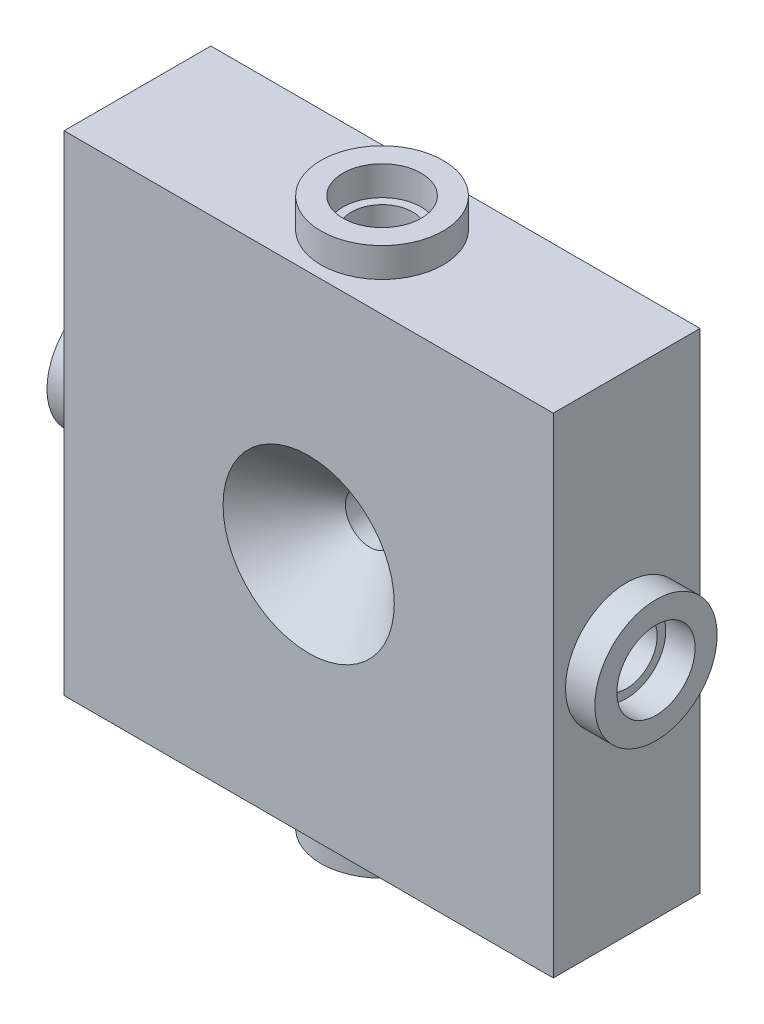
SolidWorks part; units mm, degrees
material "6063-T5"
ref_plane "正面" through (0, 0, 0) normal (0, 0, 1) x (1, 0, 0)
ref_plane "平面" through (0, 0, 0) normal (0, 1, 0) x (1, 0, 0)
ref_plane "右側面" through (0, 0, 0) normal (1, 0, 0) x (0, 0, -1)
sketch "ｽｹｯﾁ1" plane through (0, 0, 0) normal (0, 0, 1) x (1, 0, 0)
  line L1 (-10, 10) -> (10, 10)
  line L2 (-10, 10) -> (-10, -10)
  line L3 (-10, -10) -> (10, -10)
  line L4 (10, 10) -> (10, -10)
  line L5 (-10, 10) -> (10, -10) construction
  line L6 (-10, -10) -> (10, 10) construction
  circle A0 centre (0, 0) radius 1
  point P0 (0, 0)
  dimension "D2" = 2
  dimension "D1" = 20
extrude "ﾎﾞｽ - 押し出し1" add sketch "ｽｹｯﾁ1" along normal blind 3
sketch "ｽｹｯﾁ2" plane through (0, 0, 0) normal (0, 1, 0) x (1, 0, 0)
  line L1 (-1, -0.5) -> (-4.5, -3) construction
  line L2 (1, 0) -> (-1, 0) construction
  line L3 (1, 0) -> (-1, 0) construction
  line L4 (1, -0.5) -> (0, -0.5)
  line L5 (10, -3) -> (-10, -3) construction
  line L6 (0, -3) -> (3.5, -3)
  line L7 (3.5, -3) -> (1, -0.5)
  line L8 (0, -0.5) -> (0, -3)
  line L9 (-4.5, -3) -> (0, -3) construction
  line L10 (0, -0.5) -> (-1, -0.5) construction
  dimension "D2" = 45
  dimension "D3" = 0.5
  dimension "D1" = 2
revolve "ｶｯﾄ - 回転1" cut sketch "ｽｹｯﾁ2" angle 360 about L8
mirror "ﾐﾗｰ1" about plane through (0, 0, 0) normal (0, 0, 1) of bodies 103
hole_wizard "M3x0.5 ねじ穴1" positions "ｽｹｯﾁ4" profile "ｽｹｯﾁ5" tap size "M3x0.5" standard "JIS"
sketch "ｽｹｯﾁ4" plane through (-10, 0, 0) normal (-1, 0, 0) x (0, 0, 1)
  point P0 (0, 0)
sketch "ｽｹｯﾁ5" plane through (-10, 0, 0) normal (0, 1, 0) x (0, 0, 1)
  line L0 (0, 0) -> (0, 6.7511)
  line L1 (0, 6.7511) -> (1.25, 6)
  line L2 (1.25, 6) -> (1.25, 0)
  line L5 (1.25, 0) -> (0, 0)
  line L10 (0, 6.7511) -> (-1.25, 6) construction
  line L11 (0, -6.35) -> (0, 107.95) construction
  dimension "ねじ下穴ﾄﾞﾘﾙ直径" = 2.5
  dimension "ねじ下穴ﾄﾞﾘﾙの深さ" = 6
  dimension "ﾄﾞﾘﾙ角度" = 118
cosmetic thread "穴のねじ山1" parameters "D1"=6, "D2"=3
pattern_circular "円形ﾊﾟﾀｰﾝ1" count 4 over 360 about axis through (0, 0, 3) along (0, 0, -1) of "M3x0.5 ねじ穴1"
sketch "ｽｹｯﾁ6" plane through (0, 10, 0) normal (0, 1, 0) x (1, 0, 0)
  circle A0 centre (0, 0) radius 2.5
  circle A1 centre (0, 0) radius 1.6
  dimension "D1" = 3.2
  dimension "D2" = 5
extrude "ﾎﾞｽ - 押し出し2" add sketch "ｽｹｯﾁ6" along normal blind 1.2 separate body
pattern_circular "円形ﾊﾟﾀｰﾝ2" count 4 over 360 about axis through (0, 0, 0) along (0, 0, 1) of bodies 107
